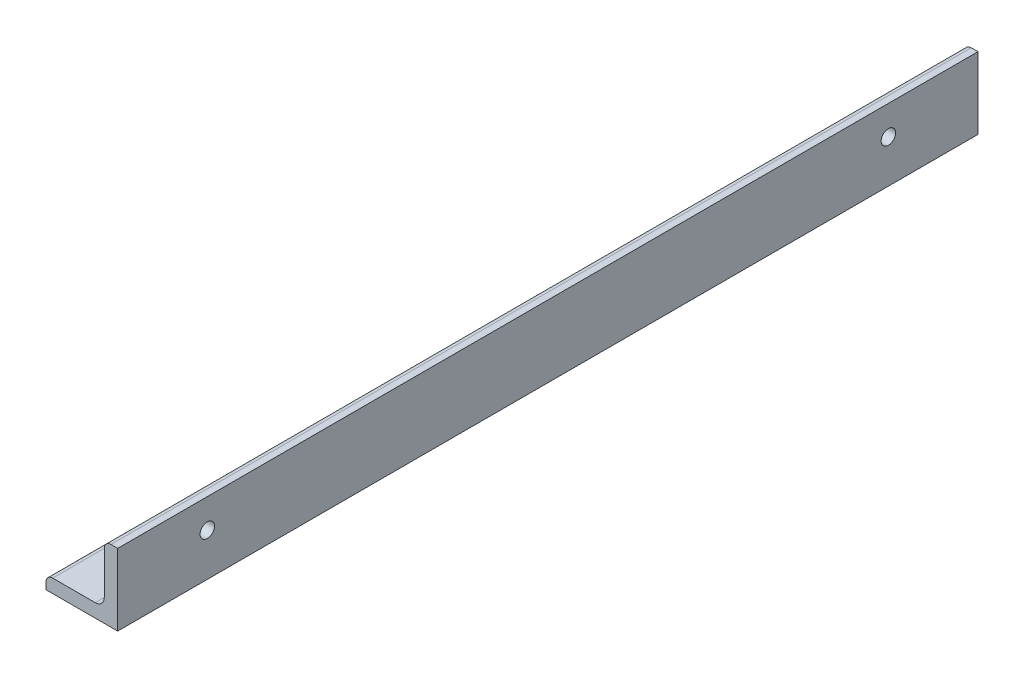
SolidWorks part; units mm, degrees
ref_plane "Front Plane" through (0, 0, 0) normal (0, 0, 1) x (1, 0, 0)
ref_plane "Top Plane" through (0, 0, 0) normal (0, 1, 0) x (1, 0, 0)
ref_plane "Right Plane" through (0, 0, 0) normal (1, 0, 0) x (0, 0, -1)
sketch "Sketch2" plane through (0, 0, 0) normal (0, 0, 1) x (1, 0, 0)
  line L0 (-12.7, 0) -> (12.7, 0)
  line L1 (12.7, 0) -> (12.7, 25.4)
  line L2 (12.7, 25.4) -> (7.9375, 25.4) construction
  line L3 (7.9375, 23.0188) -> (7.9375, 7.9375)
  line L4 (4.7625, 4.7625) -> (-10.3187, 4.7625)
  line L5 (-12.7, 0) -> (-12.7, 4.7625) construction
  line L6 (10.3187, 25.4) -> (12.7, 25.4)
  line L7 (-12.7, 2.3812) -> (-12.7, 0)
  arc A0 (7.9375, 23.0188) -> (10.3187, 25.4) centre (10.3187, 23.0188) cw
  arc A1 (-12.7, 2.3812) -> (-10.3187, 4.7625) centre (-10.3187, 2.3812) cw
  arc A2 (7.9375, 7.9375) -> (4.7625, 4.7625) centre (4.7625, 7.9375) cw
  dimension "Inside Radius" = 3.175
  dimension "Vert" = 25.4
  dimension "Horz" = 25.4
  dimension "Thickness" = 4.7625
extrude "Boss-Extrude1" add sketch "Sketch2" along normal mid plane 304.8
sketch "Break Locations" plane through (0, 0, 0) normal (1, 0, 0) x (0, 0, -1)
  line L1 (-152.4, 0) -> (-152.4, 25.4) construction
  line L2 (152.4, 0) -> (152.4, 25.4) construction
  point P0 (-130.81, 0)
  point P1 (130.81, 0)
  dimension "D1" = 21.59
  dimension "D2" = 21.59
ref_plane "Contact Plane 1" through (0, 4.7625, 0) normal (0, 1, 0) x (1, 0, 0)
ref_plane "Contact Plane 2" through (7.9375, 0, 0) normal (-1, 0, 0) x (0, 0, 1)
sketch "Sketch3" plane through (12.7, 0, 0) normal (1, 0, 0) x (0, 0, -1)
  line L0 (-152.4, 25.4) -> (152.4, 25.4) construction
  line L1 (-152.4, 0) -> (-152.4, 25.4) construction
  line L2 (152.4, 0) -> (152.4, 25.4) construction
  point P0 (-101.6, 15.113)
  point P1 (101.6, 15.113)
  point P4 (0, 0)
  dimension "D1" = 10.287
  dimension "D2" = 50.8
  dimension "D3" = 50.8
hole_wizard "#10 Clearance Hole2" positions "Sketch8" profile "Sketch9" hole size "#10" standard "ANSI Inch" end condition through all
sketch "Sketch8" plane through (12.7, 0, 0) normal (1, 0, 0) x (0, 0, -1)
  line L0 (-152.4, 25.4) -> (152.4, 25.4) construction
  line L1 (-152.4, 0) -> (-152.4, 25.4) construction
  line L2 (152.4, 0) -> (152.4, 25.4) construction
  point P0 (-120.65, 15.113)
  point P2 (120.65, 15.113)
  point P5 (0, 0)
  dimension "D1" = 10.287
  dimension "D2" = 31.75
  dimension "D3" = 31.75
sketch "Sketch9" plane through (12.7, 15.113, 120.65) normal (0, 1, 0) x (0, 0, -1)
  line L0 (0, 0) -> (0, 25.4)
  line L1 (0, 25.4) -> (2.5527, 25.4)
  line L2 (2.5527, 25.4) -> (2.5527, 0)
  line L5 (2.5527, 0) -> (0, 0)
  line L11 (0, -6.35) -> (0, 107.95) construction
  dimension "Thru Hole Dia." = 5.1054
  dimension "Thru Hole Depth" = 25.4
hole_wizard "#10 Clearance Hole3" positions "Sketch10" profile "Sketch11" hole size "#10" standard "ANSI Inch" end condition through all
sketch "Sketch10" plane through (0, 0, 0) normal (0, -1, 0) x (-1, 0, 0)
  line L0 (12.7, -152.4) -> (12.7, 152.4) construction
  line L1 (12.7, -152.4) -> (-12.7, -152.4) construction
  line L2 (12.7, 152.4) -> (-12.7, 152.4) construction
  point P0 (2.413, -120.65)
  point P2 (2.413, 120.65)
  point P11 (0, 0)
  dimension "D1" = 10.287
  dimension "D2" = 31.75
  dimension "D3" = 31.75
sketch "Sketch11" plane through (-2.413, 0, 120.65) normal (1, 0, 0) x (0, 0, -1)
  line L0 (0, 0) -> (0, 25.4)
  line L1 (0, 25.4) -> (2.5527, 25.4)
  line L2 (2.5527, 25.4) -> (2.5527, 0)
  line L5 (2.5527, 0) -> (0, 0)
  line L11 (0, -6.35) -> (0, 107.95) construction
  dimension "Thru Hole Dia." = 5.1054
  dimension "Thru Hole Depth" = 25.4
equation "\"D1@Break Locations\"=.85*\"Vert@Sketch2\""
equation "\"D2@Break Locations\"=\"D1@Break Locations\""
